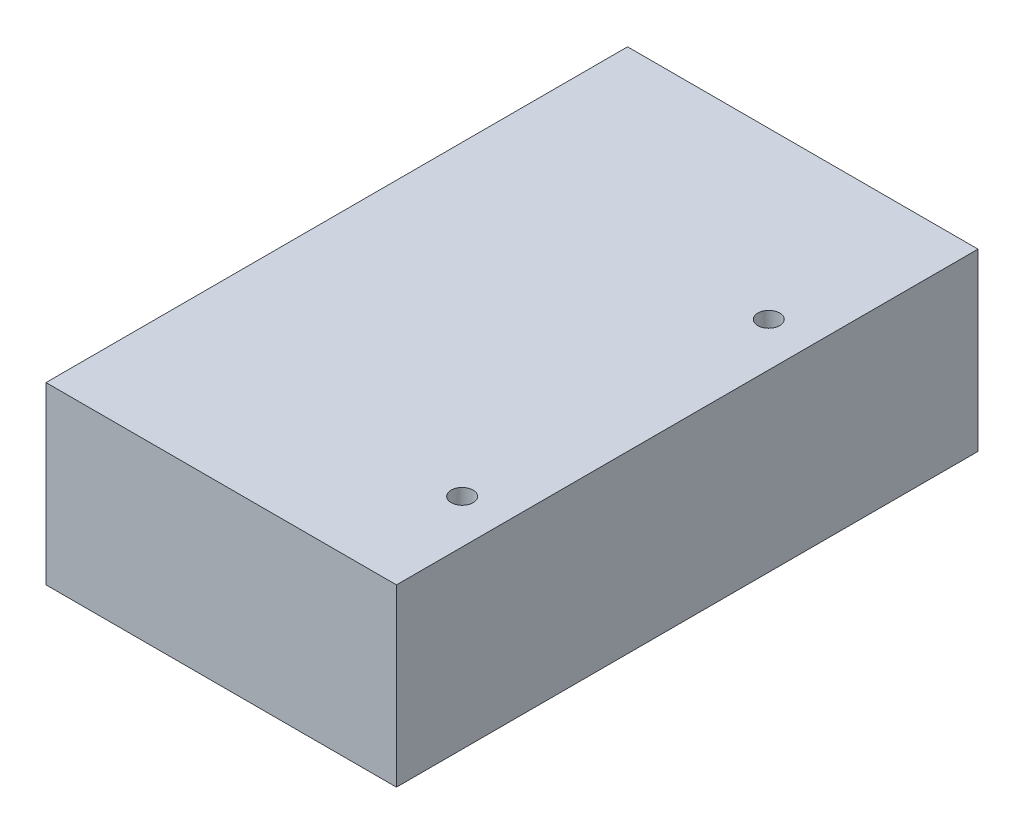
SolidWorks part; units mm, degrees
ref_plane "Front Plane" through (0, 0, 0) normal (0, 0, 1) x (1, 0, 0)
ref_plane "Top Plane" through (0, 0, 0) normal (0, 1, 0) x (1, 0, 0)
ref_plane "Right Plane" through (0, 0, 0) normal (1, 0, 0) x (0, 0, -1)
sketch "Sketch1" plane through (0, 0, 0) normal (0, 1, 0) x (1, 0, 0)
  line L1 (0, 0) -> (50.8, 0)
  line L2 (0, 0) -> (0, 76.2)
  line L3 (0, 76.2) -> (50.8, 76.2)
  line L4 (50.8, 0) -> (50.8, 76.2)
  dimension "D1" = 50.8
  dimension "D2" = 76.2
extrude "Boss-Extrude1" add sketch "Sketch1" along normal blind 25.4
sketch "Sketch2" plane through (0, 25.4, 0) normal (0, 1, 0) x (1, 0, 0)
  line L0 (44.45, 60.325) -> (44.45, 15.875) construction
  line L2 (50.8, 0) -> (50.8, 76.2) construction
  line L3 (44.45, 38.1) -> (50.8, 38.1) construction
  circle A0 centre (44.45, 60.325) radius 1.5875
  circle A1 centre (44.45, 15.875) radius 1.5875
  dimension "D1" = 3.175
  dimension "D2" = 44.45
  dimension "D3" = 6.35
extrude "Cut-Extrude1" cut sketch "Sketch2" against normal through all
sketch "Sketch3" plane through (0, 0, -76.2) normal (0, 0, 1) x (1, 0, 0)
  line L1 (0, 25.4) -> (50.8, 25.4)
  line L2 (0, 25.4) -> (0, 0)
  line L3 (0, 0) -> (50.8, 0)
  line L4 (50.8, 25.4) -> (50.8, 0)
extrude "Boss-Extrude2" add sketch "Sketch3" against normal blind 8.1026
